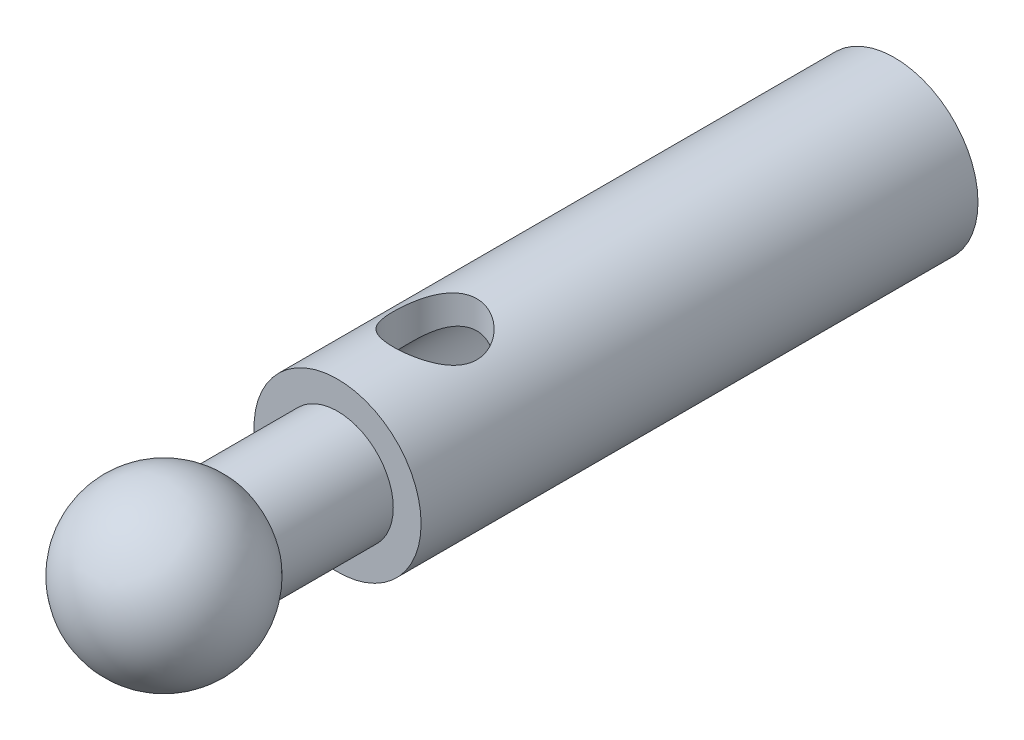
SolidWorks part; units mm, degrees
ref_plane "Piano frontale" through (0, 0, 0) normal (0, 0, 1) x (1, 0, 0)
ref_plane "Piano superiore" through (0, 0, 0) normal (0, 1, 0) x (1, 0, 0)
ref_plane "Piano destro" through (0, 0, 0) normal (1, 0, 0) x (0, 0, -1)
sketch "Schizzo1" plane through (0, 0, 0) normal (1, 0, 0) x (0, 0, -1)
  line L0 (-6.2288, 0) -> (66.6402, 0) construction
  line L1 (8.3892, 1.5) -> (-1.6108, 1.5)
  line L2 (-1.6108, 1.5) -> (-1.6108, 1)
  line L3 (8.3892, 1.5) -> (8.3892, 1)
  line L4 (-1.6108, 1) -> (-3.6108, 1)
  line L5 (8.3892, 1) -> (-0.6108, 1)
  line L6 (-0.6108, 1) -> (-0.6108, 0)
  line L7 (-6.2288, 0) -> (-0.6108, 0)
  line L8 (0, 55) -> (0, -55) construction
  arc A0 (-3.6108, 1) -> (-6.2288, 0) centre (-4.7288, 0) ccw
  dimension "D1" = 3
  dimension "D2" = 2
  dimension "D3" = 10
  dimension "D4" = 2
  dimension "D5" = 9
  dimension "D6" = 3
  dimension "D7" = 0.6108
  dimension "D8" = 4.7288
revolve "Rivoluzione1" add sketch "Schizzo1" angle 360 about L0
sketch "Schizzo2" plane through (0, 0, 0) normal (0, 1, 0) x (1, 0, 0)
  line L0 (-1, -1.6108) -> (1, -1.6108) construction
  line L1 (0, -1.65) -> (0, 1.65) construction
  circle A0 centre (0, 0.1392) radius 0.75
  dimension "D1" = 1.5
  dimension "D2" = 1.75
extrude "Taglio-Estrusione1" cut sketch "Schizzo2" against normal through all and the other way through all
